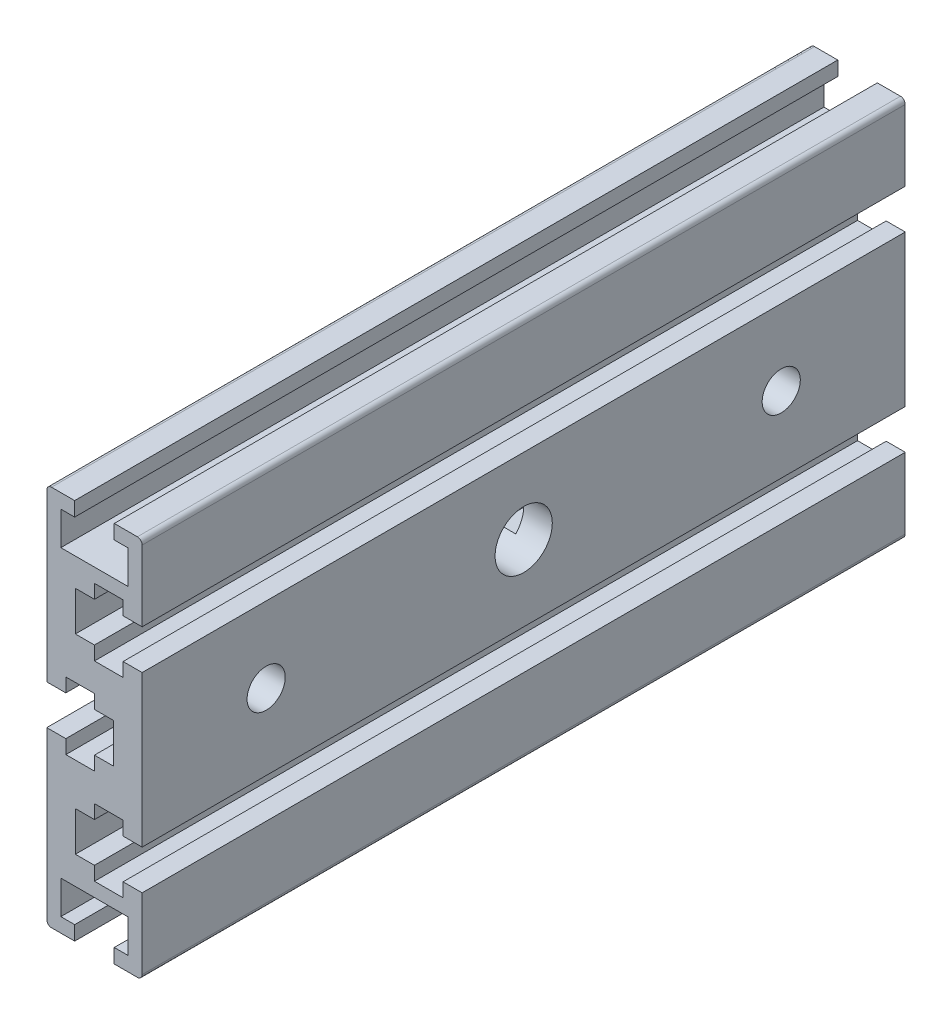
SolidWorks part; units mm, degrees
ref_plane "Plane1" through (0, 0, 0) normal (0, 0, 1) x (1, 0, 0)
ref_plane "Plane2" through (0, 0, 0) normal (0, 1, 0) x (1, 0, 0)
ref_plane "Plane3" through (0, 0, 0) normal (1, 0, 0) x (0, 0, -1)
sketch "Sketch1" plane through (0, 0, 0) normal (0, 0, 1) x (1, 0, 0)
  line L0 (0, 0) -> (75.649, 0) construction
  line L1 (-9, 40) -> (-4.15, 40)
  line L2 (-10, 39) -> (-10, 4.15)
  line L3 (-9, -40) -> (-4.15, -40)
  line L4 (10, 39) -> (10, 24.15)
  line L5 (0, 3.6903) -> (0, 44.6054) construction
  line L6 (-4.15, 40) -> (-4.15, 37)
  line L7 (-4.15, 37) -> (-7.05, 37)
  line L8 (-7.05, 37) -> (-7.05, 30)
  line L9 (-7.05, 30) -> (7.05, 30)
  line L10 (7.05, 30) -> (7.05, 37)
  line L11 (7.05, 37) -> (4.15, 37)
  line L12 (4.15, 37) -> (4.15, 40)
  line L13 (4.15, 40) -> (9, 40)
  line L14 (4.15, -37) -> (4.15, -40)
  line L15 (7.05, -37) -> (4.15, -37)
  line L16 (7.05, -30) -> (7.05, -37)
  line L17 (-7.05, -30) -> (7.05, -30)
  line L18 (-7.05, -37) -> (-7.05, -30)
  line L19 (-4.15, -37) -> (-7.05, -37)
  line L20 (-4.15, -40) -> (-4.15, -37)
  line L21 (4.15, -40) -> (9, -40)
  line L22 (-6, -7.05) -> (0, -7.05)
  line L23 (-10, -4.15) -> (-6, -4.15)
  line L24 (-6, 4.15) -> (-10, 4.15)
  line L25 (0, -7.05) -> (0, -4.15)
  line L26 (-6, -4.15) -> (-6, -7.05)
  line L27 (0, 7.05) -> (-6, 7.05)
  line L28 (-17.4711, 20) -> (26.2798, 20) construction
  line L29 (-6, 7.05) -> (-6, 4.15)
  line L30 (-17.4711, -20) -> (26.2798, -20) construction
  line L31 (-4, -15.85) -> (-4, -24.15)
  line L32 (0, -27.05) -> (0, -24.15)
  line L33 (6, -15.85) -> (10, -15.85)
  line L34 (6, -24.15) -> (6, -27.05)
  line L35 (0, -15.85) -> (0, -12.95)
  line L36 (0, 4.15) -> (4, 4.15)
  line L37 (4, 4.15) -> (4, -4.15)
  line L38 (4, -4.15) -> (0, -4.15)
  line L39 (0, 4.15) -> (0, 7.05)
  line L40 (-10, -4.15) -> (-10, -39)
  line L41 (6, 12.95) -> (6, 15.85)
  line L42 (6, 27.05) -> (0, 27.05)
  line L43 (0, 12.95) -> (6, 12.95)
  line L44 (-4, 24.15) -> (0, 24.15)
  line L45 (10, 24.15) -> (6, 24.15)
  line L46 (0, 15.85) -> (-4, 15.85)
  line L47 (0, 15.85) -> (0, 12.95)
  line L48 (6, 24.15) -> (6, 27.05)
  line L49 (0, -15.85) -> (-4, -15.85)
  line L50 (6, 15.85) -> (10, 15.85)
  line L51 (0, 27.05) -> (0, 24.15)
  line L52 (10, -24.15) -> (6, -24.15)
  line L53 (-4, 15.85) -> (-4, 24.15)
  line L54 (-4, -24.15) -> (0, -24.15)
  line L55 (0, -12.95) -> (6, -12.95)
  line L56 (6, -27.05) -> (0, -27.05)
  line L57 (6, -12.95) -> (6, -15.85)
  line L58 (10, 15.85) -> (10, -15.85)
  line L59 (10, -24.15) -> (10, -39)
  arc A0 (9, -40) -> (10, -39) centre (9, -39) ccw
  arc A1 (-10, -39) -> (-9, -40) centre (-9, -39) ccw
  arc A2 (-9, 40) -> (-10, 39) centre (-9, 39) ccw
  arc A3 (9, 40) -> (10, 39) centre (9, 39) cw
  point P72 (-10, 40)
  point P73 (10, 40)
  point P74 (0, 40)
  point P75 (-10, -40)
  point P76 (10, -40)
  point P77 (0, -40)
  point P78 (10, -20)
  point P79 (-10, 0)
  point P80 (10, 20)
  point P81 (-10, 20)
  point P82 (10, 0)
  point P83 (-10, -20)
extrude "凸台-拉伸1" add sketch "Sketch1" along normal blind 160
hole_wizard "Ø8.0 (8) 直径孔1" positions "草图2" profile "草图1" hole size "Ø8.0" standard "Gb" end condition through all
sketch "草图2" plane through (10, 0, 0) normal (1, 0, 0) x (0, 0, -1)
  line L0 (-160, -15.85) -> (-160, 15.85) construction
  line L2 (-160, -40) -> (0, -40) construction
  point P0 (-134, 0)
  dimension "D1" = 26
  dimension "D2" = 40
sketch "草图1" plane through (10, 0, 134) normal (0, 1, 0) x (0, 0, -1)
  line L0 (0, 0) -> (0, 20)
  line L1 (0, 20) -> (4, 20)
  line L2 (4, 20) -> (4, 0)
  line L5 (4, 0) -> (0, 0)
  line L11 (0, -6.35) -> (0, 107.95) construction
  dimension "通孔孔直径" = 8
  dimension "通孔孔深度" = 20
hole_wizard "Ø8.0 (8) 直径孔2" positions "草图4" profile "草图3" hole size "Ø8.0" standard "Gb"
sketch "草图4" plane through (10, 0, 0) normal (1, 0, 0) x (0, 0, -1)
  line L2 (-160, -40) -> (0, -40) construction
  point P0 (-26, 0)
  dimension "D1" = 134
  dimension "D2" = 40
sketch "草图3" plane through (10, 0, 26) normal (0, 1, 0) x (0, 0, -1)
  line L0 (0, 0) -> (0, 10.4034)
  line L1 (0, 10.4034) -> (4, 8)
  line L2 (4, 8) -> (4, 0)
  line L5 (4, 0) -> (0, 0)
  line L10 (0, 10.4034) -> (-4, 8) construction
  line L11 (0, -6.35) -> (0, 107.95) construction
  dimension "孔直径" = 8
  dimension "孔深度" = 8
  dimension "导头角度" = 118
hole_wizard "Ø12.0 (12) 直径孔2" positions "草图8" profile "草图7" hole size "Ø12.0" standard "Gb" end condition through all
sketch "草图8" plane through (10, 0, 0) normal (1, 0, 0) x (0, 0, -1)
  line L0 (-160, -39) -> (-160, -24.15) construction
  line L2 (-160, -40) -> (0, -40) construction
  point P0 (-80, 0)
  dimension "D1" = 80
  dimension "D2" = 40
sketch "草图7" plane through (10, 0, 80) normal (0, 1, 0) x (0, 0, -1)
  line L0 (0, 0) -> (0, 20)
  line L1 (0, 20) -> (6, 20)
  line L2 (6, 20) -> (6, 0)
  line L5 (6, 0) -> (0, 0)
  line L11 (0, -6.35) -> (0, 107.95) construction
  dimension "通孔孔直径" = 12
  dimension "通孔孔深度" = 20
